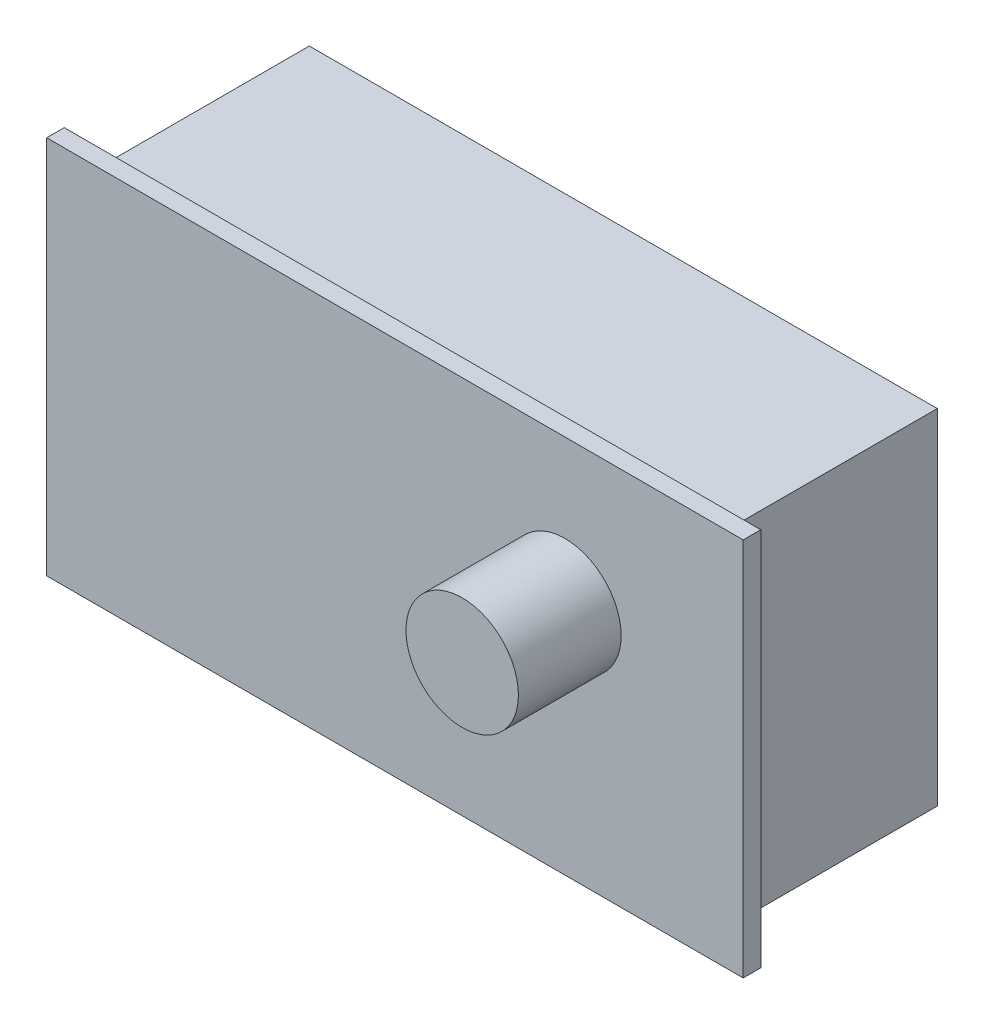
SolidWorks part; units mm, degrees
ref_plane "Plan de face" through (0, 0, 0) normal (0, 0, 1) x (1, 0, 0)
ref_plane "Plan de dessus" through (0, 0, 0) normal (0, 1, 0) x (1, 0, 0)
ref_plane "Plan de droite" through (0, 0, 0) normal (1, 0, 0) x (0, 0, -1)
sketch "Esquisse1" plane through (0, 0, 0) normal (0, 0, 1) x (1, 0, 0)
  line L1 (0, 0) -> (71.5, 0)
  line L2 (0, 0) -> (0, -39.2)
  line L3 (0, -39.2) -> (71.5, -39.2)
  line L4 (71.5, 0) -> (71.5, -39.2)
  dimension "D1" = 71.5
  dimension "D2" = 39.2
extrude "Boss.-Extru.1" add sketch "Esquisse1" along normal blind 24
sketch "Esquisse2" plane through (0, 0, 24) normal (0, 0, 1) x (1, 0, 0)
  line L0 (71.5, -39.2) -> (71.5, 0) construction
  line L1 (-3.9, 2) -> (75.4, 2)
  line L2 (-3.9, 2) -> (-3.9, -41.2)
  line L3 (-3.9, -41.2) -> (75.4, -41.2)
  line L4 (75.4, 2) -> (75.4, -41.2)
  line L5 (0, 0) -> (0, -39.2) construction
  line L6 (71.5, 0) -> (0, 0) construction
  line L7 (0, -39.2) -> (71.5, -39.2) construction
  dimension "D1" = 3.9
  dimension "D2" = 3.9
  dimension "D3" = 2
  dimension "D4" = 2
extrude "Boss.-Extru.2" add sketch "Esquisse2" along normal blind 2
sketch "Esquisse3" plane through (0, 0, 26) normal (0, 0, 1) x (1, 0, 0)
  line L2 (75.4, 2) -> (-3.9, 2) construction
  circle A0 centre (55.1057, -14.4) radius 6.4
  dimension "D2" = 12.8
  dimension "D1" = 16.4
extrude "Boss.-Extru.3" add sketch "Esquisse3" along normal blind 11.7
